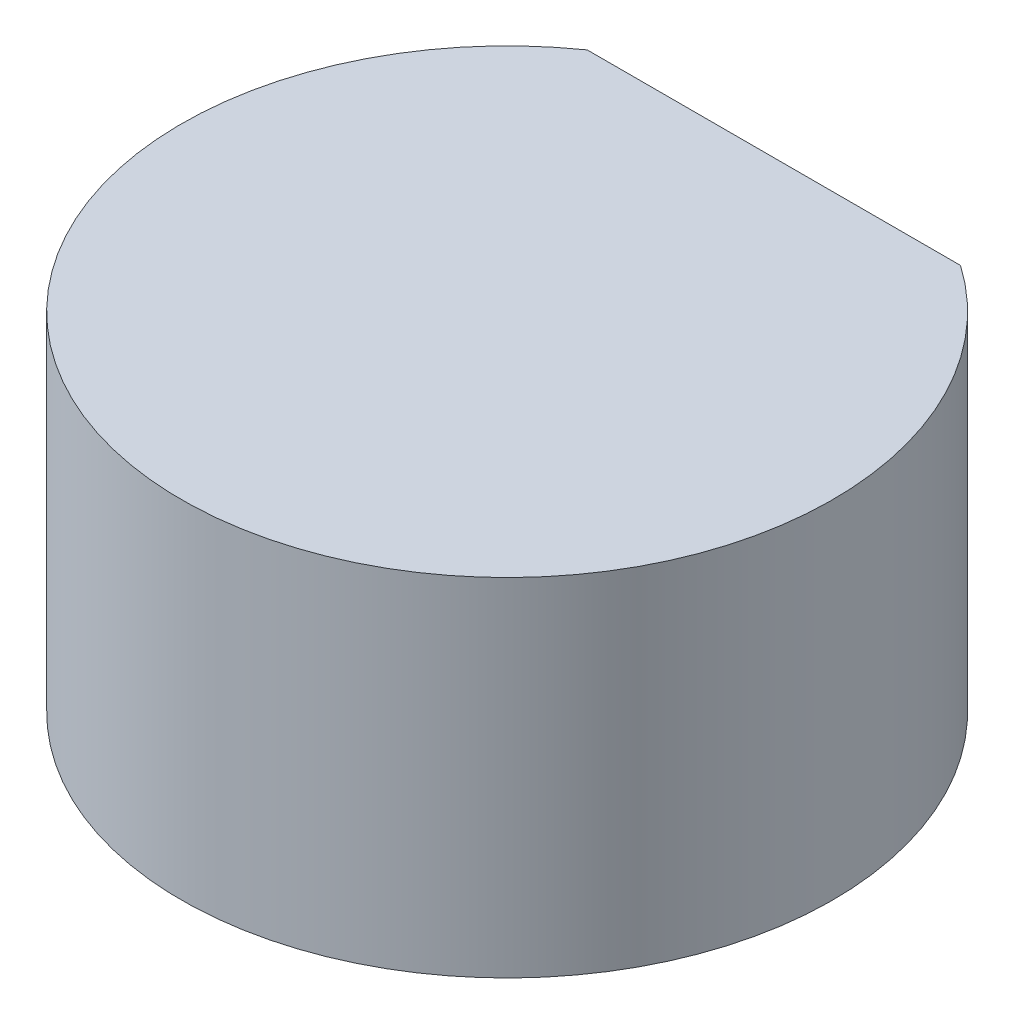
SolidWorks part; units mm, degrees
material "ABS"
ref_plane "Front Plane" through (0, 0, 0) normal (0, 0, 1) x (1, 0, 0)
ref_plane "Top Plane" through (0, 0, 0) normal (0, 1, 0) x (1, 0, 0)
ref_plane "Right Plane" through (0, 0, 0) normal (1, 0, 0) x (0, 0, -1)
sketch "Sketch1" plane through (0, 0, 0) normal (0, 1, 0) x (1, 0, 0)
  line L0 (-44.4297, 63.5) -> (44.4297, 63.5)
  arc A0 (-44.4297, 63.5) -> (44.4297, 63.5) centre (0, 0) ccw
  dimension "D1" = 155
  dimension "D2" = 63.5
extrude "Boss-Extrude1" add sketch "Sketch1" along normal blind 82.55
sketch "Sketch2" plane through (0, 0, 0) normal (0, -1, 0) x (1, 0, 0)
  line L0 (44.4297, -63.5) -> (-44.4297, -63.5) construction
  line L1 (0, 28.3486) -> (0, -15.8491) construction
  circle A0 centre (-27, -27.5) radius 2
  circle A1 centre (-27, 26.5) radius 2
  circle A2 centre (21, 30.5) radius 2
  circle A3 centre (27, -27.5) radius 2
  dimension "D3" = 4
  dimension "D1" = 36
  dimension "D2" = 27
  dimension "D4" = 90
  dimension "D5" = 94
  dimension "D6" = 48
extrude "Cut-Extrude1" cut sketch "Sketch2" against normal blind 5
sketch "Sketch3" plane through (0, 0, -63.5) normal (0, 0, -1) x (-1, 0, 0)
  line L0 (-44.4297, 0) -> (44.4297, 0) construction
  line L1 (-7.1813, 42.5) -> (24.3187, 42.5)
  line L2 (-7.1813, 42.5) -> (-7.1813, 19)
  line L3 (-7.1813, 19) -> (24.3187, 19)
  line L4 (24.3187, 42.5) -> (24.3187, 19)
  line L5 (-7.1813, 42.5) -> (24.3187, 19) construction
  line L6 (-7.1813, 19) -> (24.3187, 42.5) construction
  line L7 (-77.5, 0) -> (77.5, 0) construction
  line L8 (77.5, 82.55) -> (-77.5, 82.55) construction
  line L9 (-77.5, 0) -> (77.5, 0) construction
  line L10 (77.5, 82.55) -> (-77.5, 82.55) construction
  line L11 (77.5, 82.55) -> (77.5, 0) construction
  point P0 (8.5688, 30.75)
  dimension "D1" = 19
  dimension "D2" = 23.5
  dimension "D3" = 31.5
  dimension "D4" = 53.1812
extrude "Boss-Extrude2" add sketch "Sketch3" along normal blind 15
